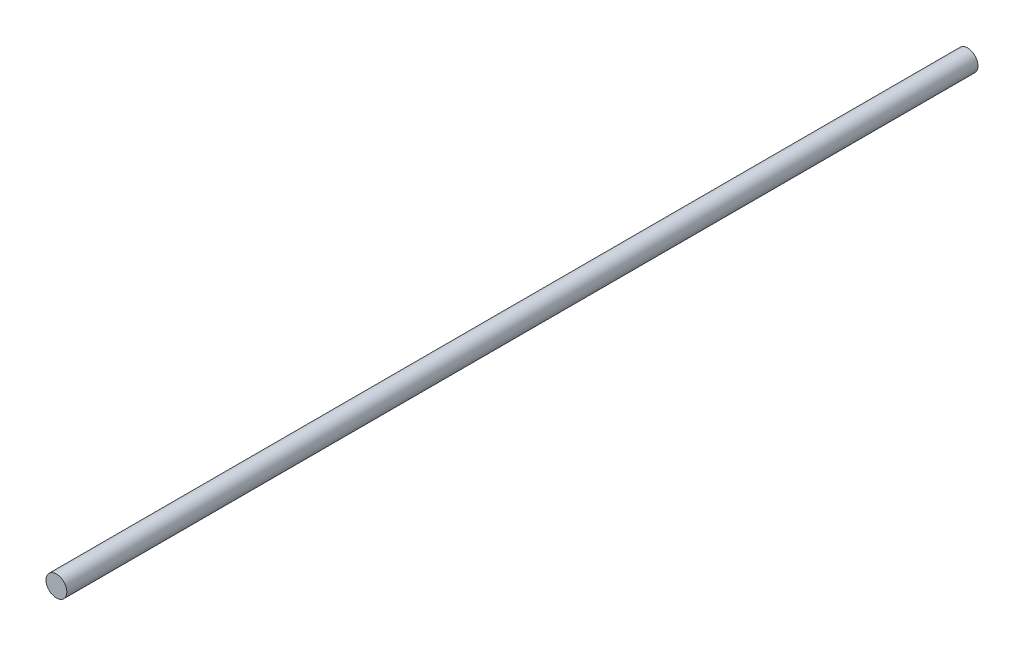
SolidWorks part; units mm, degrees
ref_plane "Front Plane" through (0, 0, 0) normal (0, 0, 1) x (1, 0, 0)
ref_plane "Top Plane" through (0, 0, 0) normal (0, 1, 0) x (1, 0, 0)
ref_plane "Right Plane" through (0, 0, 0) normal (1, 0, 0) x (0, 0, -1)
sketch "Sketch2" plane through (0, 0, 0) normal (0, 0, 1) x (1, 0, 0)
  circle A0 centre (0, 0) radius 4
extrude "Boss-Extrude1" add sketch "Sketch2" along normal blind 350
